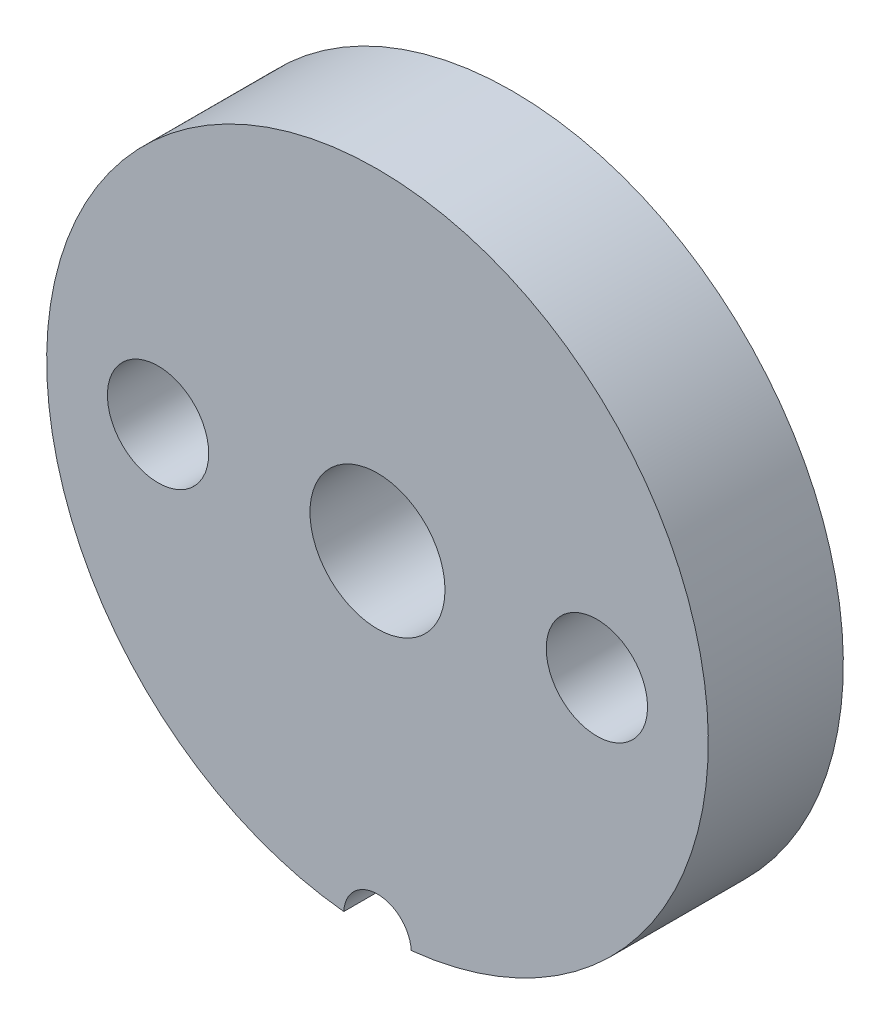
SolidWorks part; units mm, degrees
ref_plane "前视基准面" through (0, 0, 0) normal (0, 0, 1) x (1, 0, 0)
ref_plane "上视基准面" through (0, 0, 0) normal (0, 1, 0) x (1, 0, 0)
ref_plane "右视基准面" through (0, 0, 0) normal (1, 0, 0) x (0, 0, -1)
sketch "草图1" plane through (0, 0, 0) normal (0, 0, 1) x (1, 0, 0)
  line L0 (0.7836, -0.3918) -> (0.7836, -3.8918) construction
  line L1 (0.7836, -3.8918) -> (-5.7164, -3.8918) construction
  circle A0 centre (-5.7164, -3.8918) radius 1.5
  circle A1 centre (7.2836, -3.8918) radius 1.5
  circle A2 centre (0.7836, -3.8918) radius 2
  circle A4 centre (0.7836, -3.8918) radius 9.8
  dimension "D3" = 19.6
  dimension "D1" = 3.5
  dimension "D2" = 6.5
extrude "凸台-拉伸1" add sketch "草图1" along normal blind 4
sketch "草图2" plane through (0, 0, 4) normal (0, 0, 1) x (1, 0, 0)
  circle A0 centre (0.7836, -13.6918) radius 1
  circle A1 centre (0.7836, -3.8918) radius 9.8 construction
extrude "切除-拉伸1" cut sketch "草图2" against normal blind 10
